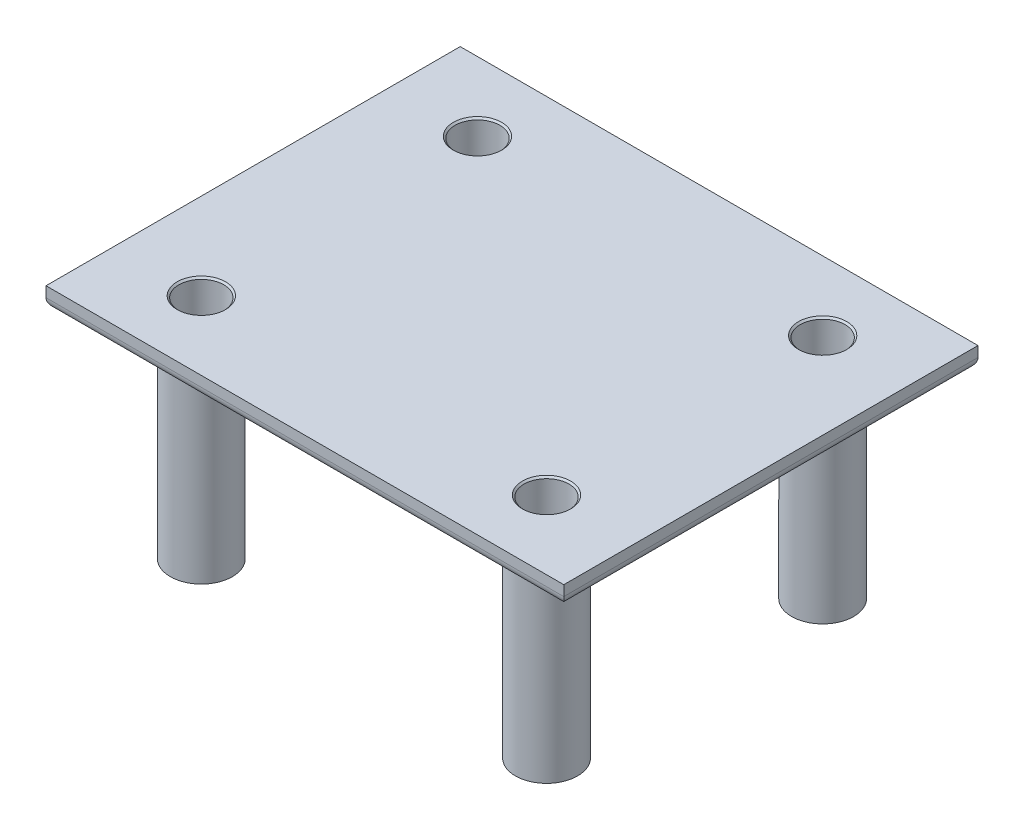
SolidWorks part; units mm, degrees
ref_plane "前视基准面" through (0, 0, 0) normal (0, 0, 1) x (1, 0, 0)
ref_plane "上视基准面" through (0, 0, 0) normal (0, 1, 0) x (1, 0, 0)
ref_plane "右视基准面" through (0, 0, 0) normal (1, 0, 0) x (0, 0, -1)
sketch "草图1" plane through (0, 0, 0) normal (0, 1, 0) x (1, 0, 0)
  line L1 (-75, 60) -> (75, 60)
  line L2 (-75, 60) -> (-75, -60)
  line L3 (-75, -60) -> (75, -60)
  line L4 (75, 60) -> (75, -60)
  line L5 (-75, 60) -> (75, -60) construction
  line L6 (-75, -60) -> (75, 60) construction
  point P0 (0, 0)
  dimension "D1" = 120
  dimension "D2" = 150
extrude "凸台-拉伸1" add sketch "草图1" along normal blind 6
sketch "草图2" plane through (0, 0, 0) normal (0, -1, 0) x (1, 0, 0)
  line L0 (-78.7, 0) -> (77.1807, 0) construction
  line L1 (0, 48.086) -> (0, -47.0225) construction
  line L2 (50, 40) -> (-50, 40) construction
  line L3 (-50, 40) -> (-50, -40) construction
  line L4 (50, -40) -> (-50, -40) construction
  line L5 (50, 40) -> (50, -40) construction
  circle A0 centre (-50, 40) radius 9
  circle A1 centre (50, 40) radius 9
  circle A2 centre (50, -40) radius 9
  circle A3 centre (-50, -40) radius 9
  point P9 (-50, 0)
  point P11 (0, -40)
  point P12 (0, 40)
  dimension "D3" = 18
  dimension "D1" = 80
  dimension "D2" = 100
extrude "凸台-拉伸2" add sketch "草图2" along normal blind 60
sketch "草图3" plane through (0, 0, 0) normal (0, -1, 0) x (1, 0, 0)
  line L0 (-45.9639, 48.0443) -> (-10, 30)
  line L1 (-10, 30) -> (10, 30)
  line L2 (-10, 9.8614) -> (-10, -9.8614)
  line L3 (-10, -30) -> (10, -30)
  line L4 (10, 9.8614) -> (10, -9.8614)
  line L5 (-10, 30) -> (10, -30) construction
  line L6 (-10, -30) -> (10, 30) construction
  line L12 (-81.7932, 0) -> (81.0542, 0) construction
  line L13 (0, 65.3414) -> (0, -68.4966) construction
  line L18 (-54.0361, 31.9557) -> (-10, 9.8614)
  line L28 (-45.9639, 48.0443) -> (-54.0361, 31.9557)
  line L38 (45.9639, 48.0443) -> (54.0361, 31.9557)
  line L48 (54.0361, 31.9557) -> (10, 9.8614)
  line L49 (45.9639, 48.0443) -> (10, 30)
  line L50 (45.9639, -48.0443) -> (10, -30)
  line L51 (54.0361, -31.9557) -> (10, -9.8614)
  line L52 (45.9639, -48.0443) -> (54.0361, -31.9557)
  line L53 (-45.9639, -48.0443) -> (-54.0361, -31.9557)
  line L54 (-54.0361, -31.9557) -> (-10, -9.8614)
  line L55 (-10, -30) -> (10, -30)
  line L56 (-45.9639, -48.0443) -> (-10, -30)
  circle A1 centre (-50, 40) radius 9 construction
  circle A2 centre (-50, 40) radius 9 construction
  point P0 (0, 0)
  circle M3 centre (50, -40) radius 9
  circle M4 centre (-50, 40) radius 9
  circle M5 centre (-50, -40) radius 9
  circle M6 centre (50, 40) radius 9
  dimension "D1" = 60
  dimension "D2" = 20
extrude "凸台-拉伸3" add sketch "草图3" along normal blind 5 contours L56 L3 L50 L51 L4 L48 L49 L1 L0 L18 L2 L54 M5 M3 M6 M4
sketch "草图4" plane through (0, -60, 0) normal (0, -1, 0) x (1, 0, 0)
  circle A0 centre (-50, 40) radius 6.5
  circle A1 centre (50, -40) radius 6.5
  circle A2 centre (50, 40) radius 6.5
  circle A3 centre (-50, -40) radius 6.5
  dimension "D1" = 13
extrude "切除-拉伸1" cut sketch "草图4" against normal through all
sketch "草图5" plane through (0, 0, 0) normal (1, 0, 0) x (0, 0, -1)
  line L1 (-20, -5) -> (20, -5)
  line L2 (-31.9557, -5) -> (-9.8614, -5) construction
  line L4 (-4, -4) -> (4, -4)
  line L5 (0, 0) -> (0, -10.329) construction
  arc A3 (-4, -4) -> (-20, -5) centre (-6.7455, -88.5724) ccw
  arc A4 (4, -4) -> (20, -5) centre (6.7455, -88.5724) cw
  point P5 (0, -4)
  dimension "D1" = 40
  dimension "D2" = 1
  dimension "D3" = 8
extrude "切除-拉伸2" cut sketch "草图5" against normal mid plane 13
fillet "圆角1" radius 2 16 edges at (58.0443, 0, -44.0361) (-58.0443, 0, -44.0361) (-58.0443, 0, 44.0361) (58.0443, 0, 44.0361) (27.982, 0, -39.0221) (32.018, 0, -20.9086) (-32.018, 0, -20.9086) (-27.982, 0, -39.0221) (-27.982, 0, 39.0221) (-32.018, 0, 20.9086) (32.018, 0, 20.9086) (27.982, 0, 39.0221) (-10, 0, 0) (10, 0, 0) (0, -5, -20) (0, -5, 20)
fillet "圆角3" radius 3 4 edges at (-75, 0, 0) (0, 0, 60) (0, 0, -60) (75, 0, 0)
chamfer "倒角1" distance 1 angle 45 4 edges at (-50, -60, -46.5) (-50, -60, 33.5) (50, -60, -46.5) (50, -60, 33.5)
chamfer "倒角2" distance 0.5 angle 45 4 edges at (-50, 6, 33.5) (-50, 6, -46.5) (50, 6, -46.5) (50, 6, 33.5)
